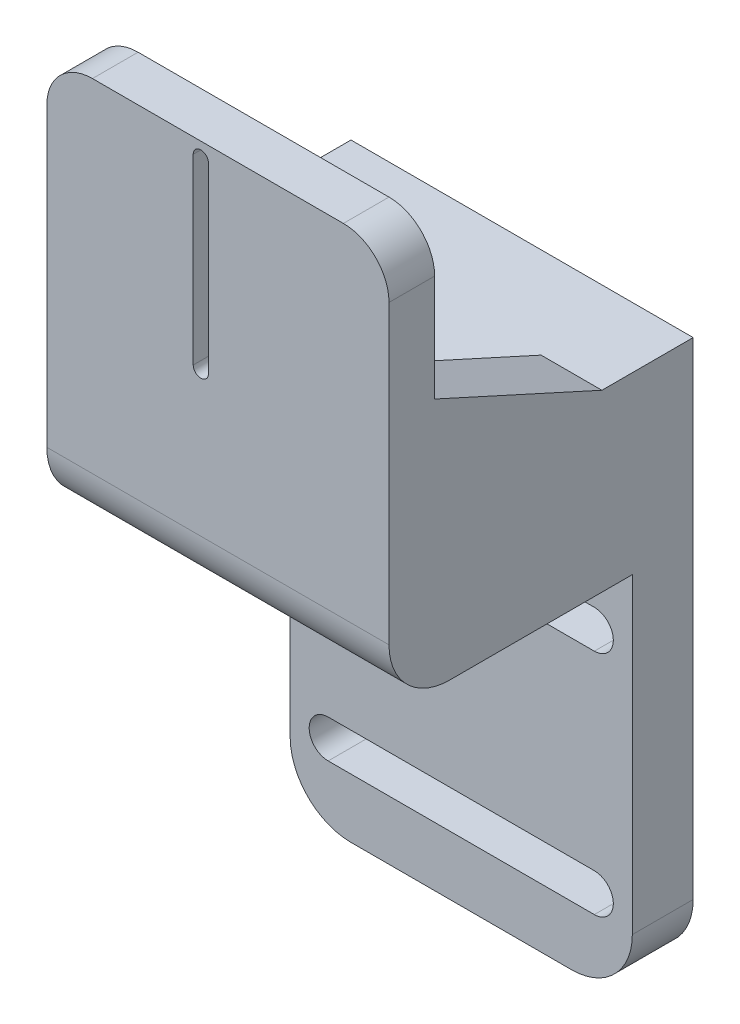
SolidWorks part; units mm, degrees
ref_plane "前视基准面" through (0, 0, 0) normal (0, 0, 1) x (1, 0, 0)
ref_plane "上视基准面" through (0, 0, 0) normal (0, 1, 0) x (1, 0, 0)
ref_plane "右视基准面" through (0, 0, 0) normal (1, 0, 0) x (0, 0, -1)
other "Configuration Table"
sketch "草图1" plane through (0, 0, 0) normal (0, 0, 1) x (1, 0, 0)
  line L1 (26.5206, -44.9834) -> (71.5206, -44.9834)
  line L2 (26.5206, -44.9834) -> (26.5206, -116.9834)
  line L3 (26.5206, -116.9834) -> (71.5206, -116.9834)
  line L4 (71.5206, -44.9834) -> (71.5206, -116.9834)
  line L5 (26.5206, -42.9834) -> (26.5206, -55.9834) construction
  line L6 (31.5206, -76.7014) -> (66.5206, -76.7014) construction
  line L7 (31.5206, -74.2014) -> (66.5206, -74.2014)
  line L8 (31.5206, -79.2014) -> (66.5206, -79.2014)
  line L9 (31.5206, -106.7014) -> (66.5206, -106.7014) construction
  line L10 (31.5206, -104.2014) -> (66.5206, -104.2014)
  line L11 (31.5206, -109.2014) -> (66.5206, -109.2014)
  line L12 (21.5206, -104.2014) -> (66.5206, -104.2014) construction
  line L13 (66.5206, -109.2014) -> (21.5206, -109.2014) construction
  line L14 (21.5206, -74.2014) -> (66.5206, -74.2014) construction
  line L15 (66.5206, -79.2014) -> (21.5206, -79.2014) construction
  line L17 (96.5926, -41.9834) -> (27.5206, -41.9834) construction
  arc A0 (31.5206, -74.2014) -> (31.5206, -79.2014) centre (31.5206, -76.7014) ccw
  arc A1 (66.5206, -79.2014) -> (66.5206, -74.2014) centre (66.5206, -76.7014) ccw
  arc A2 (31.5206, -104.2014) -> (31.5206, -109.2014) centre (31.5206, -106.7014) ccw
  arc A3 (66.5206, -109.2014) -> (66.5206, -104.2014) centre (66.5206, -106.7014) ccw
  point P10 (49.0206, -76.7014)
  point P15 (49.0206, -106.7014)
  dimension "D1" = 72
  dimension "D2" = 45
  dimension "D3" = 5
  dimension "D4" = 5
  dimension "D5" = 3
extrude "凸台-拉伸1" add sketch "草图1" along normal blind 8
sketch "草图3" plane through (0, 0, 8) normal (0, 0, 1) x (1, 0, 0)
  line L0 (71.5206, -116.9834) -> (71.5206, -44.9834) construction
  line L1 (26.5206, -44.9834) -> (71.5206, -44.9834)
  line L2 (26.5206, -44.9834) -> (26.5206, -67.9834)
  line L3 (26.5206, -67.9834) -> (71.5206, -67.9834)
  line L4 (71.5206, -44.9834) -> (71.5206, -67.9834)
  dimension "D1" = 23
extrude "凸台-拉伸2" add sketch "草图3" along normal blind 32
sketch "草图4" plane through (0, -44.9834, 0) normal (0, 1, 0) x (1, 0, 0)
  line L0 (71.5206, -40) -> (71.5206, 0) construction
  line L1 (26.5206, -40) -> (71.5206, -40)
  line L2 (26.5206, -40) -> (26.5206, -34)
  line L3 (26.5206, -34) -> (71.5206, -34)
  line L4 (71.5206, -40) -> (71.5206, -34)
  dimension "D1" = 6
extrude "凸台-拉伸3" add sketch "草图4" along normal blind 30
sketch "草图5" plane through (0, 0, 40) normal (0, 0, 1) x (1, 0, 0)
  line L14 (45.7706, -23.6565) -> (45.7706, -38.6565) construction
  line L15 (46.7706, -16.9834) -> (46.7706, -40.9834) construction
  line L18 (47.7706, -16.9834) -> (47.7706, -40.9834)
  line L19 (45.7706, -16.9834) -> (45.7706, -40.9834)
  line L20 (26.5206, -14.9834) -> (71.5206, -14.9834) construction
  line L21 (71.5206, -67.9834) -> (71.5206, -14.9834) construction
  arc A5 (47.7706, -16.9834) -> (45.7706, -16.9834) centre (46.7706, -16.9834) ccw
  arc A6 (45.7706, -40.9834) -> (47.7706, -40.9834) centre (46.7706, -40.9834) ccw
  point P22 (46.7706, -28.9834)
  dimension "D2" = 1
  dimension "D1" = 2
  dimension "D3" = 26
  dimension "D4" = 23.75
extrude "切除-拉伸1" cut sketch "草图5" against normal up to surface (6 mm away) up to face at (49.0206, -29.9834, 34)
fillet "圆角1" radius 8 2 edges at (71.5206, -116.9834, 4) (26.5206, -116.9834, 4)
sketch "草图7" plane through (71.5206, 0, 0) normal (1, 0, 0) x (0, 0, -1)
  line L0 (-34, -34.9834) -> (-12, -44.9834)
  line L1 (-34, -14.9834) -> (-34, -44.9834) construction
  line L2 (-34, -44.9834) -> (0, -44.9834) construction
  dimension "D1" = 10
  dimension "D2" = 22
rib "筋1" sketch "草图7" sketch "草图7" thickness 8 extrusion direction parallel to sketch draft on no parameters "D1"=8
fillet "圆角2" radius 8 1 edges at (49.0206, -67.9834, 40)
fillet "圆角3" radius 6 2 edges at (71.5206, -14.9834, 37) (26.5206, -14.9834, 37)
sketch "草图8" plane through (26.5206, 0, 0) normal (-1, 0, 0) x (0, 0, 1)
  line L1 (34, -34.9834) -> (12, -44.9834) construction
  line L2 (34, -34.9834) -> (12, -44.9834)
